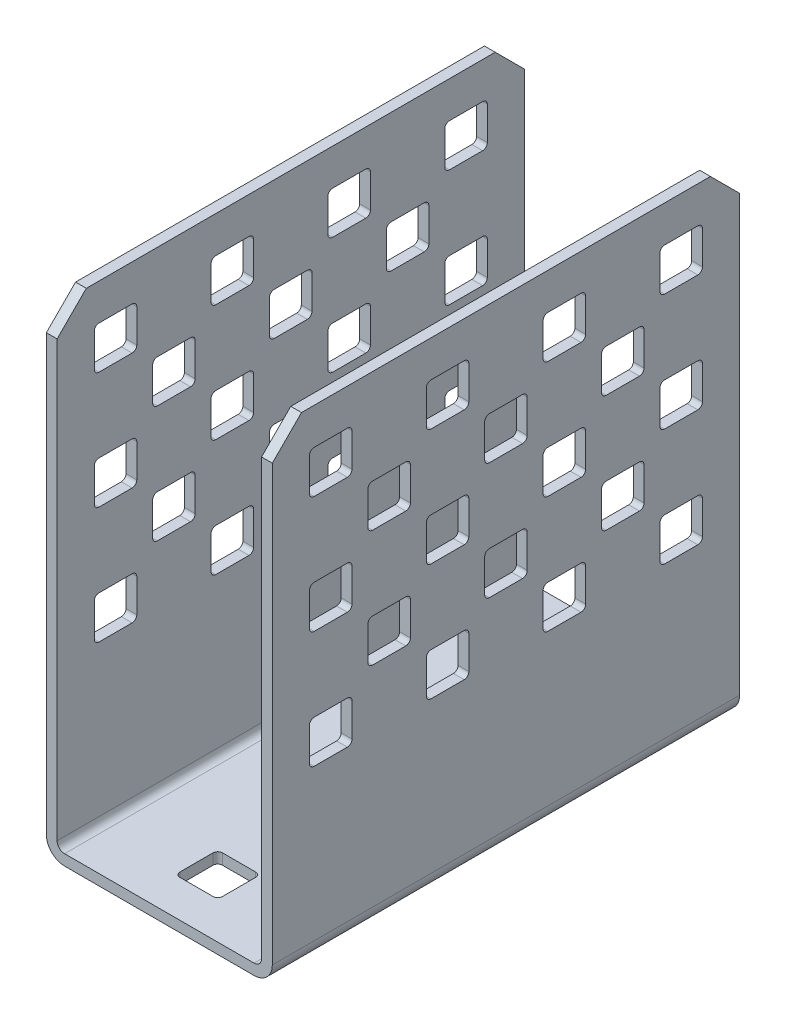
SolidWorks part; units mm, degrees
ref_plane "Front Plane" through (0, 0, 0) normal (0, 0, 1) x (1, 0, 0)
ref_plane "Top Plane" through (0, 0, 0) normal (0, 1, 0) x (1, 0, 0)
ref_plane "Right Plane" through (0, 0, 0) normal (1, 0, 0) x (0, 0, -1)
ref_plane "Plane1" through (12.2809, 0, 0) normal (1, 0, 0) x (0, 0, -1)
sketch "Sketch1" plane through (12.2809, 0, 0) normal (1, 0, 0) x (0, 0, -1)
  line L0 (25.4, 52.4002) -> (-25.4, 52.4002)
  line L1 (-25.4, 52.4002) -> (-25.4, 0)
  line L2 (-25.4, 0) -> (25.4, 0)
  line L3 (25.4, 0) -> (25.4, 52.4002)
extrude "Boss-Extrude1" add sketch "Sketch1" against normal blind 24.5618
sketch "Sketch2" plane through (0, 0, -25.4) normal (0, 0, -1) x (-1, 0, 0)
  line L0 (11.1125, 52.4002) -> (-11.1125, 52.4002)
  line L1 (-11.1125, 52.4002) -> (-11.1125, 1.1684)
  line L2 (-11.1125, 1.1684) -> (11.1125, 1.1684)
  line L3 (11.1125, 1.1684) -> (11.1125, 52.4002)
extrude "Cut-Extrude1" cut sketch "Sketch2" against normal through all
sketch "Sketch3" plane through (-12.2809, 0, 0) normal (-1, 0, 0) x (0, 0, 1)
  line L0 (-21.3614, 18.415) -> (-16.7386, 18.415)
  line L1 (-16.7386, 18.415) -> (-16.7386, 23.0378)
  line L2 (-16.7386, 23.0378) -> (-21.3614, 23.0378)
  line L3 (-21.3614, 23.0378) -> (-21.3614, 18.415)
extrude "Cut-Extrude2" cut sketch "Sketch3" against normal up to next
sketch "Sketch4" plane through (-12.2809, 0, 0) normal (-1, 0, 0) x (0, 0, 1)
  line L0 (4.0386, 18.415) -> (8.6614, 18.415)
  line L1 (8.6614, 18.415) -> (8.6614, 23.0378)
  line L2 (8.6614, 23.0378) -> (4.0386, 23.0378)
  line L3 (4.0386, 23.0378) -> (4.0386, 18.415)
extrude "Cut-Extrude3" cut sketch "Sketch4" against normal up to next
sketch "Sketch5" plane through (-12.2809, 0, 0) normal (-1, 0, 0) x (0, 0, 1)
  line L0 (-15.0114, 24.765) -> (-10.3886, 24.765)
  line L1 (-10.3886, 24.765) -> (-10.3886, 29.3878)
  line L2 (-10.3886, 29.3878) -> (-15.0114, 29.3878)
  line L3 (-15.0114, 29.3878) -> (-15.0114, 24.765)
extrude "Cut-Extrude4" cut sketch "Sketch5" against normal up to next
sketch "Sketch6" plane through (-12.2809, 0, 0) normal (-1, 0, 0) x (0, 0, 1)
  line L0 (10.3886, 24.765) -> (15.0114, 24.765)
  line L1 (15.0114, 24.765) -> (15.0114, 29.3878)
  line L2 (15.0114, 29.3878) -> (10.3886, 29.3878)
  line L3 (10.3886, 29.3878) -> (10.3886, 24.765)
extrude "Cut-Extrude5" cut sketch "Sketch6" against normal up to next
sketch "Sketch7" plane through (-12.2809, 0, 0) normal (-1, 0, 0) x (0, 0, 1)
  line L0 (16.7386, 43.815) -> (21.3614, 43.815)
  line L1 (21.3614, 43.815) -> (21.3614, 48.4378)
  line L2 (21.3614, 48.4378) -> (16.7386, 48.4378)
  line L3 (16.7386, 48.4378) -> (16.7386, 43.815)
extrude "Cut-Extrude6" cut sketch "Sketch7" against normal up to next
sketch "Sketch8" plane through (-12.2809, 0, 0) normal (-1, 0, 0) x (0, 0, 1)
  line L0 (16.7386, 31.115) -> (21.3614, 31.115)
  line L1 (21.3614, 31.115) -> (21.3614, 35.7378)
  line L2 (21.3614, 35.7378) -> (16.7386, 35.7378)
  line L3 (16.7386, 35.7378) -> (16.7386, 31.115)
extrude "Cut-Extrude7" cut sketch "Sketch8" against normal up to next
sketch "Sketch9" plane through (-12.2809, 0, 0) normal (-1, 0, 0) x (0, 0, 1)
  line L0 (10.3886, 42.0878) -> (10.3886, 37.465)
  line L1 (10.3886, 37.465) -> (15.0114, 37.465)
  line L2 (15.0114, 37.465) -> (15.0114, 42.0878)
  line L3 (15.0114, 42.0878) -> (10.3886, 42.0878)
extrude "Cut-Extrude8" cut sketch "Sketch9" against normal up to next
sketch "Sketch10" plane through (-12.2809, 0, 0) normal (-1, 0, 0) x (0, 0, 1)
  line L0 (4.0386, 35.7378) -> (4.0386, 31.115)
  line L1 (4.0386, 31.115) -> (8.6614, 31.115)
  line L2 (8.6614, 31.115) -> (8.6614, 35.7378)
  line L3 (8.6614, 35.7378) -> (4.0386, 35.7378)
extrude "Cut-Extrude9" cut sketch "Sketch10" against normal up to next
sketch "Sketch11" plane through (-12.2809, 0, 0) normal (-1, 0, 0) x (0, 0, 1)
  line L0 (4.0386, 48.4378) -> (4.0386, 43.815)
  line L1 (4.0386, 43.815) -> (8.6614, 43.815)
  line L2 (8.6614, 43.815) -> (8.6614, 48.4378)
  line L3 (8.6614, 48.4378) -> (4.0386, 48.4378)
extrude "Cut-Extrude10" cut sketch "Sketch11" against normal up to next
sketch "Sketch12" plane through (-12.2809, 0, 0) normal (-1, 0, 0) x (0, 0, 1)
  line L0 (-2.3114, 42.0878) -> (-2.3114, 37.465)
  line L1 (-2.3114, 37.465) -> (2.3114, 37.465)
  line L2 (2.3114, 37.465) -> (2.3114, 42.0878)
  line L3 (2.3114, 42.0878) -> (-2.3114, 42.0878)
extrude "Cut-Extrude11" cut sketch "Sketch12" against normal up to next
sketch "Sketch13" plane through (-12.2809, 0, 0) normal (-1, 0, 0) x (0, 0, 1)
  line L0 (-8.6614, 35.7378) -> (-8.6614, 31.115)
  line L1 (-8.6614, 31.115) -> (-4.0386, 31.115)
  line L2 (-4.0386, 31.115) -> (-4.0386, 35.7378)
  line L3 (-4.0386, 35.7378) -> (-8.6614, 35.7378)
extrude "Cut-Extrude12" cut sketch "Sketch13" against normal up to next
sketch "Sketch14" plane through (-12.2809, 0, 0) normal (-1, 0, 0) x (0, 0, 1)
  line L0 (-8.6614, 48.4378) -> (-8.6614, 43.815)
  line L1 (-8.6614, 43.815) -> (-4.0386, 43.815)
  line L2 (-4.0386, 43.815) -> (-4.0386, 48.4378)
  line L3 (-4.0386, 48.4378) -> (-8.6614, 48.4378)
extrude "Cut-Extrude13" cut sketch "Sketch14" against normal up to next
sketch "Sketch15" plane through (-12.2809, 0, 0) normal (-1, 0, 0) x (0, 0, 1)
  line L0 (-15.0114, 42.0878) -> (-15.0114, 37.465)
  line L1 (-15.0114, 37.465) -> (-10.3886, 37.465)
  line L2 (-10.3886, 37.465) -> (-10.3886, 42.0878)
  line L3 (-10.3886, 42.0878) -> (-15.0114, 42.0878)
extrude "Cut-Extrude14" cut sketch "Sketch15" against normal up to next
sketch "Sketch16" plane through (-12.2809, 0, 0) normal (-1, 0, 0) x (0, 0, 1)
  line L0 (-21.3614, 35.7378) -> (-21.3614, 31.115)
  line L1 (-21.3614, 31.115) -> (-16.7386, 31.115)
  line L2 (-16.7386, 31.115) -> (-16.7386, 35.7378)
  line L3 (-16.7386, 35.7378) -> (-21.3614, 35.7378)
extrude "Cut-Extrude15" cut sketch "Sketch16" against normal up to next
sketch "Sketch17" plane through (-12.2809, 0, 0) normal (-1, 0, 0) x (0, 0, 1)
  line L0 (-21.3614, 48.4378) -> (-21.3614, 43.815)
  line L1 (-21.3614, 43.815) -> (-16.7386, 43.815)
  line L2 (-16.7386, 43.815) -> (-16.7386, 48.4378)
  line L3 (-16.7386, 48.4378) -> (-21.3614, 48.4378)
extrude "Cut-Extrude16" cut sketch "Sketch17" against normal up to next
sketch "Sketch18" plane through (-12.2809, 0, 0) normal (-1, 0, 0) x (0, 0, 1)
  line L0 (-2.3114, 24.765) -> (2.3114, 24.765)
  line L1 (2.3114, 24.765) -> (2.3114, 29.3878)
  line L2 (2.3114, 29.3878) -> (-2.3114, 29.3878)
  line L3 (-2.3114, 29.3878) -> (-2.3114, 24.765)
extrude "Cut-Extrude17" cut sketch "Sketch18" against normal up to next
sketch "Sketch19" plane through (-12.2809, 0, 0) normal (-1, 0, 0) x (0, 0, 1)
  line L0 (16.7386, 18.415) -> (21.3614, 18.415)
  line L1 (21.3614, 18.415) -> (21.3614, 23.0378)
  line L2 (21.3614, 23.0378) -> (16.7386, 23.0378)
  line L3 (16.7386, 23.0378) -> (16.7386, 18.415)
extrude "Cut-Extrude18" cut sketch "Sketch19" against normal up to next
sketch "Sketch20" plane through (0, 1.1684, 0) normal (0, 1, 0) x (-1, 0, 0)
  line L0 (-2.3114, -21.3614) -> (2.3114, -21.3614)
  line L1 (2.3114, -21.3614) -> (2.3114, -16.7386)
  line L2 (2.3114, -16.7386) -> (-2.3114, -16.7386)
  line L3 (-2.3114, -16.7386) -> (-2.3114, -21.3614)
extrude "Cut-Extrude19" cut sketch "Sketch20" against normal through all
sketch "Sketch21" plane through (0, 1.1684, 0) normal (0, 1, 0) x (-1, 0, 0)
  line L0 (-2.3114, -8.6614) -> (2.3114, -8.6614)
  line L1 (2.3114, -8.6614) -> (2.3114, -4.0386)
  line L2 (2.3114, -4.0386) -> (-2.3114, -4.0386)
  line L3 (-2.3114, -4.0386) -> (-2.3114, -8.6614)
extrude "Cut-Extrude20" cut sketch "Sketch21" against normal through all
sketch "Sketch22" plane through (0, 1.1684, 0) normal (0, 1, 0) x (-1, 0, 0)
  line L0 (-2.3114, 16.7386) -> (2.3114, 16.7386)
  line L1 (2.3114, 16.7386) -> (2.3114, 21.3614)
  line L2 (2.3114, 21.3614) -> (-2.3114, 21.3614)
  line L3 (-2.3114, 21.3614) -> (-2.3114, 16.7386)
extrude "Cut-Extrude21" cut sketch "Sketch22" against normal through all
sketch "Sketch23" plane through (11.1125, 0, 0) normal (-1, 0, 0) x (0, 0, 1)
  line L0 (-16.7386, 23.0378) -> (-21.3614, 23.0378)
  line L1 (-21.3614, 23.0378) -> (-21.3614, 18.415)
  line L2 (-21.3614, 18.415) -> (-16.7386, 18.415)
  line L3 (-16.7386, 18.415) -> (-16.7386, 23.0378)
extrude "Cut-Extrude22" cut sketch "Sketch23" against normal through all
sketch "Sketch24" plane through (11.1125, 0, 0) normal (-1, 0, 0) x (0, 0, 1)
  line L0 (8.6614, 23.0378) -> (4.0386, 23.0378)
  line L1 (4.0386, 23.0378) -> (4.0386, 18.415)
  line L2 (4.0386, 18.415) -> (8.6614, 18.415)
  line L3 (8.6614, 18.415) -> (8.6614, 23.0378)
extrude "Cut-Extrude23" cut sketch "Sketch24" against normal through all
sketch "Sketch25" plane through (11.1125, 0, 0) normal (-1, 0, 0) x (0, 0, 1)
  line L0 (-10.3886, 29.3878) -> (-15.0114, 29.3878)
  line L1 (-15.0114, 29.3878) -> (-15.0114, 24.765)
  line L2 (-15.0114, 24.765) -> (-10.3886, 24.765)
  line L3 (-10.3886, 24.765) -> (-10.3886, 29.3878)
extrude "Cut-Extrude24" cut sketch "Sketch25" against normal through all
sketch "Sketch26" plane through (11.1125, 0, 0) normal (-1, 0, 0) x (0, 0, 1)
  line L0 (15.0114, 29.3878) -> (10.3886, 29.3878)
  line L1 (10.3886, 29.3878) -> (10.3886, 24.765)
  line L2 (10.3886, 24.765) -> (15.0114, 24.765)
  line L3 (15.0114, 24.765) -> (15.0114, 29.3878)
extrude "Cut-Extrude25" cut sketch "Sketch26" against normal through all
sketch "Sketch27" plane through (11.1125, 0, 0) normal (-1, 0, 0) x (0, 0, 1)
  line L0 (21.3614, 43.815) -> (21.3614, 48.4378)
  line L1 (21.3614, 48.4378) -> (16.7386, 48.4378)
  line L2 (16.7386, 48.4378) -> (16.7386, 43.815)
  line L3 (16.7386, 43.815) -> (21.3614, 43.815)
extrude "Cut-Extrude26" cut sketch "Sketch27" against normal through all
sketch "Sketch28" plane through (11.1125, 0, 0) normal (-1, 0, 0) x (0, 0, 1)
  line L0 (21.3614, 31.115) -> (21.3614, 35.7378)
  line L1 (21.3614, 35.7378) -> (16.7386, 35.7378)
  line L2 (16.7386, 35.7378) -> (16.7386, 31.115)
  line L3 (16.7386, 31.115) -> (21.3614, 31.115)
extrude "Cut-Extrude27" cut sketch "Sketch28" against normal through all
sketch "Sketch29" plane through (11.1125, 0, 0) normal (-1, 0, 0) x (0, 0, 1)
  line L0 (15.0114, 37.465) -> (15.0114, 42.0878)
  line L1 (15.0114, 42.0878) -> (10.3886, 42.0878)
  line L2 (10.3886, 42.0878) -> (10.3886, 37.465)
  line L3 (10.3886, 37.465) -> (15.0114, 37.465)
extrude "Cut-Extrude28" cut sketch "Sketch29" against normal through all
sketch "Sketch30" plane through (11.1125, 0, 0) normal (-1, 0, 0) x (0, 0, 1)
  line L0 (8.6614, 31.115) -> (8.6614, 35.7378)
  line L1 (8.6614, 35.7378) -> (4.0386, 35.7378)
  line L2 (4.0386, 35.7378) -> (4.0386, 31.115)
  line L3 (4.0386, 31.115) -> (8.6614, 31.115)
extrude "Cut-Extrude29" cut sketch "Sketch30" against normal through all
sketch "Sketch31" plane through (11.1125, 0, 0) normal (-1, 0, 0) x (0, 0, 1)
  line L0 (8.6614, 43.815) -> (8.6614, 48.4378)
  line L1 (8.6614, 48.4378) -> (4.0386, 48.4378)
  line L2 (4.0386, 48.4378) -> (4.0386, 43.815)
  line L3 (4.0386, 43.815) -> (8.6614, 43.815)
extrude "Cut-Extrude30" cut sketch "Sketch31" against normal through all
sketch "Sketch32" plane through (11.1125, 0, 0) normal (-1, 0, 0) x (0, 0, 1)
  line L0 (2.3114, 37.465) -> (2.3114, 42.0878)
  line L1 (2.3114, 42.0878) -> (-2.3114, 42.0878)
  line L2 (-2.3114, 42.0878) -> (-2.3114, 37.465)
  line L3 (-2.3114, 37.465) -> (2.3114, 37.465)
extrude "Cut-Extrude31" cut sketch "Sketch32" against normal through all
sketch "Sketch33" plane through (11.1125, 0, 0) normal (-1, 0, 0) x (0, 0, 1)
  line L0 (-4.0386, 31.115) -> (-4.0386, 35.7378)
  line L1 (-4.0386, 35.7378) -> (-8.6614, 35.7378)
  line L2 (-8.6614, 35.7378) -> (-8.6614, 31.115)
  line L3 (-8.6614, 31.115) -> (-4.0386, 31.115)
extrude "Cut-Extrude32" cut sketch "Sketch33" against normal through all
sketch "Sketch34" plane through (11.1125, 0, 0) normal (-1, 0, 0) x (0, 0, 1)
  line L0 (-4.0386, 43.815) -> (-4.0386, 48.4378)
  line L1 (-4.0386, 48.4378) -> (-8.6614, 48.4378)
  line L2 (-8.6614, 48.4378) -> (-8.6614, 43.815)
  line L3 (-8.6614, 43.815) -> (-4.0386, 43.815)
extrude "Cut-Extrude33" cut sketch "Sketch34" against normal through all
sketch "Sketch35" plane through (11.1125, 0, 0) normal (-1, 0, 0) x (0, 0, 1)
  line L0 (-10.3886, 37.465) -> (-10.3886, 42.0878)
  line L1 (-10.3886, 42.0878) -> (-15.0114, 42.0878)
  line L2 (-15.0114, 42.0878) -> (-15.0114, 37.465)
  line L3 (-15.0114, 37.465) -> (-10.3886, 37.465)
extrude "Cut-Extrude34" cut sketch "Sketch35" against normal through all
sketch "Sketch36" plane through (11.1125, 0, 0) normal (-1, 0, 0) x (0, 0, 1)
  line L0 (-16.7386, 31.115) -> (-16.7386, 35.7378)
  line L1 (-16.7386, 35.7378) -> (-21.3614, 35.7378)
  line L2 (-21.3614, 35.7378) -> (-21.3614, 31.115)
  line L3 (-21.3614, 31.115) -> (-16.7386, 31.115)
extrude "Cut-Extrude35" cut sketch "Sketch36" against normal through all
sketch "Sketch37" plane through (11.1125, 0, 0) normal (-1, 0, 0) x (0, 0, 1)
  line L0 (-16.7386, 43.815) -> (-16.7386, 48.4378)
  line L1 (-16.7386, 48.4378) -> (-21.3614, 48.4378)
  line L2 (-21.3614, 48.4378) -> (-21.3614, 43.815)
  line L3 (-21.3614, 43.815) -> (-16.7386, 43.815)
extrude "Cut-Extrude36" cut sketch "Sketch37" against normal through all
sketch "Sketch38" plane through (11.1125, 0, 0) normal (-1, 0, 0) x (0, 0, 1)
  line L0 (2.3114, 29.3878) -> (-2.3114, 29.3878)
  line L1 (-2.3114, 29.3878) -> (-2.3114, 24.765)
  line L2 (-2.3114, 24.765) -> (2.3114, 24.765)
  line L3 (2.3114, 24.765) -> (2.3114, 29.3878)
extrude "Cut-Extrude37" cut sketch "Sketch38" against normal through all
sketch "Sketch39" plane through (11.1125, 0, 0) normal (-1, 0, 0) x (0, 0, 1)
  line L0 (21.3614, 23.0378) -> (16.7386, 23.0378)
  line L1 (16.7386, 23.0378) -> (16.7386, 18.415)
  line L2 (16.7386, 18.415) -> (21.3614, 18.415)
  line L3 (21.3614, 18.415) -> (21.3614, 23.0378)
extrude "Cut-Extrude38" cut sketch "Sketch39" against normal through all
sketch "Sketch40" plane through (11.1125, 0, 0) normal (-1, 0, 0) x (0, 0, 1)
  line L0 (-4.0386, 23.0378) -> (-8.6614, 23.0378)
  line L1 (-8.6614, 23.0378) -> (-8.6614, 18.415)
  line L2 (-8.6614, 18.415) -> (-4.0386, 18.415)
  line L3 (-4.0386, 18.415) -> (-4.0386, 23.0378)
extrude "Cut-Extrude39" cut sketch "Sketch40" against normal through all
sketch "Sketch41" plane through (0, 1.1684, 0) normal (0, 1, 0) x (-1, 0, 0)
  line L0 (-2.3114, 4.0386) -> (2.3114, 4.0386)
  line L1 (2.3114, 4.0386) -> (2.3114, 8.6614)
  line L2 (2.3114, 8.6614) -> (-2.3114, 8.6614)
  line L3 (-2.3114, 8.6614) -> (-2.3114, 4.0386)
extrude "Cut-Extrude40" cut sketch "Sketch41" against normal through all
sketch "Sketch42" plane through (-11.1125, 0, 0) normal (1, 0, 0) x (0, 0, -1)
  line L0 (4.0386, 23.0378) -> (4.0386, 18.415)
  line L1 (4.0386, 18.415) -> (8.6614, 18.415)
  line L2 (8.6614, 18.415) -> (8.6614, 23.0378)
  line L3 (8.6614, 23.0378) -> (4.0386, 23.0378)
extrude "Cut-Extrude41" cut sketch "Sketch42" against normal through all
chamfer "Chamfer1" distance 3.175 angle 45 4 edges at (11.6967, 52.4002, 25.4) (11.6967, 52.4002, -25.4) (-11.6967, 52.4002, 25.4) (-11.6967, 52.4002, -25.4)
fillet "Fillet1" radius 0.508 120 edges at (-11.6967, 35.7378, 4.0386) (-11.6967, 24.765, -2.3114) (11.6967, 23.0378, 16.7386) (-11.6967, 48.4378, 21.3614) (11.6967, 23.0378, 21.3614) (-11.6967, 18.415, -8.6614) (11.6967, 18.415, 21.3614) (-11.6967, 35.7378, -21.3614) (11.6967, 24.765, -2.3114) (-11.6967, 42.0878, -2.3114) (11.6967, 29.3878, -2.3114) (11.6967, 23.0378, -4.0386) (11.6967, 29.3878, 2.3114) (-11.6967, 29.3878, -15.0114) (11.6967, 48.4378, -16.7386) (-11.6967, 48.4378, -21.3614) (11.6967, 43.815, -16.7386) (-11.6967, 42.0878, -15.0114) (11.6967, 43.815, -21.3614) (-11.6967, 35.7378, -8.6614) (11.6967, 35.7378, -21.3614) (-11.6967, 48.4378, 4.0386) (11.6967, 35.7378, -16.7386) (-11.6967, 42.0878, 10.3886) (11.6967, 31.115, -16.7386) (-11.6967, 35.7378, 21.3614) (11.6967, 31.115, -21.3614) (-11.6967, 29.3878, 10.3886) (11.6967, 42.0878, -15.0114) (11.6967, 42.0878, -10.3886) (2.3114, 0.5842, -4.0386) (11.6967, 37.465, -10.3886) (-11.6967, 23.0378, -4.0386) (11.6967, 48.4378, -8.6614) (-11.6967, 23.0378, 21.3614) (11.6967, 48.4378, -4.0386) (11.6967, 43.815, -4.0386) (-11.6967, 43.815, -16.7386) (11.6967, 43.815, -8.6614) (-11.6967, 31.115, -16.7386) (11.6967, 35.7378, -4.0386) (-11.6967, 43.815, -4.0386) (11.6967, 31.115, -8.6614) (-11.6967, 37.465, 2.3114) (11.6967, 42.0878, -2.3114) (-11.6967, 43.815, 8.6614) (-11.6967, 31.115, 8.6614) (11.6967, 37.465, 2.3114) (-11.6967, 37.465, 15.0114) (11.6967, 37.465, -2.3114) (-11.6967, 43.815, 16.7386) (11.6967, 48.4378, 8.6614) (-11.6967, 24.765, 15.0114) (11.6967, 43.815, 8.6614) (-11.6967, 18.415, 8.6614) (11.6967, 35.7378, 4.0386) (-11.6967, 18.415, -16.7386) (11.6967, 35.7378, 8.6614) (2.3114, 0.5842, -8.6614) (11.6967, 31.115, 8.6614) (-2.3114, 0.5842, -16.7386) (11.6967, 23.0378, -8.6614) (11.6967, 42.0878, 15.0114) (-11.6967, 18.415, -4.0386) (11.6967, 37.465, 15.0114) (11.6967, 35.7378, 16.7386) (-11.6967, 23.0378, 16.7386) (11.6967, 35.7378, 21.3614) (-11.6967, 24.765, 2.3114) (11.6967, 31.115, 21.3614) (-11.6967, 29.3878, -2.3114) (11.6967, 31.115, 16.7386) (-11.6967, 43.815, -21.3614) (11.6967, 48.4378, 16.7386) (-11.6967, 48.4378, -16.7386) (11.6967, 48.4378, 21.3614) (-11.6967, 37.465, -15.0114) (11.6967, 24.765, 10.3886) (-11.6967, 42.0878, -10.3886) (11.6967, 29.3878, 10.3886) (-11.6967, 43.815, -8.6614) (11.6967, 29.3878, 15.0114) (-11.6967, 48.4378, -4.0386) (11.6967, 24.765, 15.0114) (-11.6967, 31.115, -8.6614) (11.6967, 24.765, -15.0114) (-11.6967, 35.7378, -4.0386) (11.6967, 29.3878, -15.0114) (-11.6967, 37.465, -2.3114) (11.6967, 29.3878, -10.3886) (-11.6967, 42.0878, 2.3114) (11.6967, 24.765, -10.3886) (11.6967, 18.415, 4.0386) (-11.6967, 48.4378, 8.6614) (11.6967, 23.0378, 4.0386) (11.6967, 23.0378, 8.6614) (-11.6967, 35.7378, 8.6614) (11.6967, 18.415, 8.6614) (-11.6967, 37.465, 10.3886) (11.6967, 23.0378, -21.3614) (-11.6967, 35.7378, 16.7386) (11.6967, 23.0378, -16.7386) (-11.6967, 31.115, 21.3614) (-11.6967, 48.4378, 16.7386) (11.6967, 18.415, -8.6614) (-11.6967, 43.815, 21.3614) (-11.6967, 24.765, 10.3886) (-2.3114, 0.5842, 4.0386) (-11.6967, 29.3878, 15.0114) (2.3114, 0.5842, 4.0386) (-11.6967, 29.3878, -10.3886) (-2.3114, 0.5842, 21.3614) (-11.6967, 18.415, 4.0386) (-2.3114, 0.5842, 16.7386) (2.3114, 0.5842, 21.3614) (-11.6967, 18.415, -21.3614) (-11.6967, 23.0378, -21.3614) (-11.6967, 23.0378, -16.7386) (-2.3114, 0.5842, -4.0386) (2.3114, 0.5842, 16.7386)
fillet "Fillet2" radius 0.8128 2 edges at (-11.1125, 1.1684, 0) (11.1125, 1.1684, 0)
fillet "Fillet3" radius 1.9812 2 edges at (-12.2809, 0, 0) (12.2809, 0, 0)
